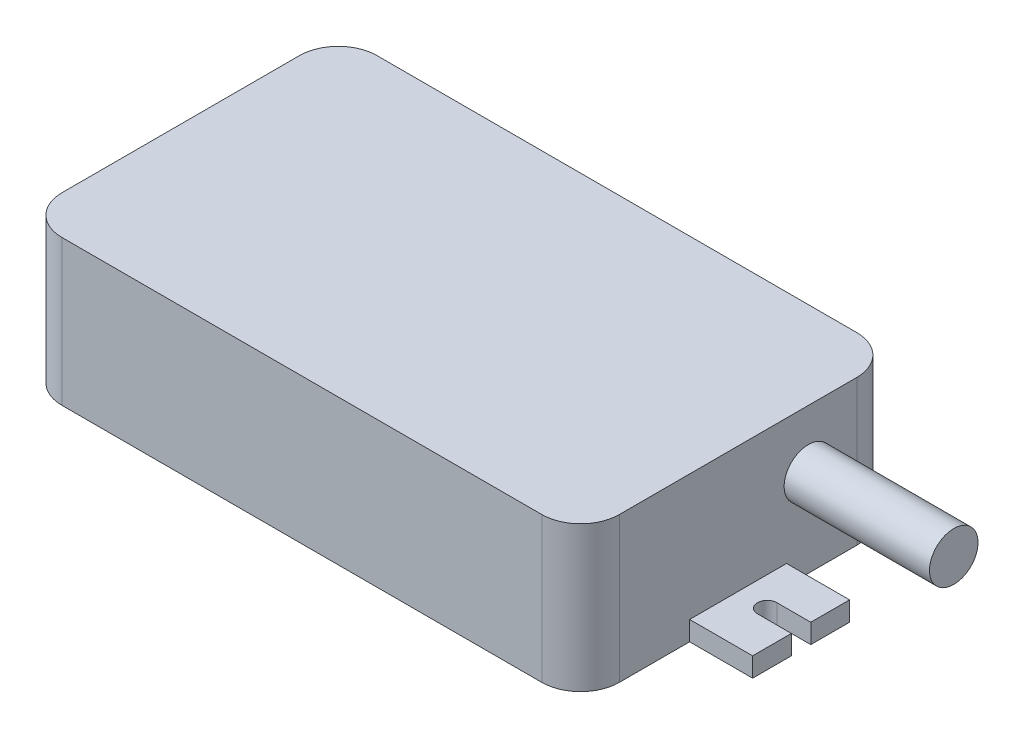
SolidWorks part; units mm, degrees
ref_plane "Front Plane" through (0, 0, 0) normal (0, 0, 1) x (1, 0, 0)
ref_plane "Top Plane" through (0, 0, 0) normal (0, 1, 0) x (1, 0, 0)
ref_plane "Right Plane" through (0, 0, 0) normal (1, 0, 0) x (0, 0, -1)
sketch "Sketch1" plane through (0, 0, 0) normal (0, 1, 0) x (1, 0, 0)
  line L0 (57.5, 32.5) -> (-57.5, -32.5) construction
  line L1 (-57.5, 32.5) -> (57.5, 32.5)
  line L2 (-57.5, 32.5) -> (-57.5, -32.5)
  line L3 (-57.5, -32.5) -> (57.5, -32.5)
  line L4 (57.5, 32.5) -> (57.5, -32.5)
  point P4 (0, 0)
  point P5 (0, 0)
  dimension "D1" = 115
  dimension "D2" = 65
extrude "Boss-Extrude1" add sketch "Sketch1" along normal blind 30
sketch "Sketch3" plane through (0, 0, 0) normal (0, -1, 0) x (1, 0, 0)
  line L0 (57.5, 32.5) -> (57.5, -32.5) construction
  line L1 (-70.5, 10) -> (70.5, 10)
  line L2 (-70.5, 10) -> (-70.5, 2)
  line L3 (-70.5, -10) -> (70.5, -10)
  line L4 (70.5, 10) -> (70.5, 2)
  line L5 (-70.5, 10) -> (70.5, -10) construction
  line L6 (-70.5, -10) -> (70.5, 10) construction
  line L7 (-57.5, -32.5) -> (-57.5, 32.5) construction
  line L8 (63.5, 2) -> (63.5, -2) construction
  line L9 (63.5, 2) -> (70.5, 2)
  line L10 (63.5, -2) -> (70.5, -2)
  line L11 (70.5, 2) -> (70.5, -2) construction
  line L12 (-63.5, 2) -> (-63.5, -2) construction
  line L13 (-63.5, 2) -> (-70.5, 2)
  line L14 (-63.5, -2) -> (-70.5, -2)
  line L15 (-70.5, 2) -> (-70.5, -2) construction
  line L16 (-70.5, 2) -> (-70.5, -2) construction
  line L17 (-70.5, -2) -> (-70.5, -10)
  line L18 (70.5, 2) -> (70.5, -2) construction
  line L19 (70.5, -2) -> (70.5, -10)
  arc A0 (63.5, 2) -> (63.5, -2) centre (63.5, 0) ccw
  arc A1 (-63.5, -2) -> (-63.5, 2) centre (-63.5, 0) ccw
  arc A2 (-63.5, 2) -> (-63.5, -2) centre (-63.5, 0) ccw construction
  arc A3 (63.5, -2) -> (63.5, 2) centre (63.5, 0) ccw construction
  point P0 (0, 0)
  point P14 (0, 0)
  point P21 (0, 0)
  point P24 (70.5, 2)
  point P25 (-70.5, 2)
  dimension "D5" = 4
  dimension "D6" = 4
  dimension "D1" = 13
  dimension "D2" = 20
  dimension "D3" = 6
  dimension "D4" = 6
extrude "Boss-Extrude2" add sketch "Sketch3" against normal blind 4
sketch "Sketch4" plane through (57.5, 0, 0) normal (1, 0, 0) x (0, 0, -1)
  line L0 (10, 0) -> (32.5, 0) construction
  line L1 (32.5, 30) -> (32.5, 0) construction
  circle A0 centre (14.5, 18) radius 5
  dimension "D2" = 10
  dimension "D1" = 18
  dimension "D3" = 18
extrude "Boss-Extrude3" add sketch "Sketch4" along normal blind 30
fillet "Fillet1" radius 8 4 edges at (-57.5, 15, 32.5) (-57.5, 15, -32.5) (57.5, 15, 32.5) (57.5, 15, -32.5)
